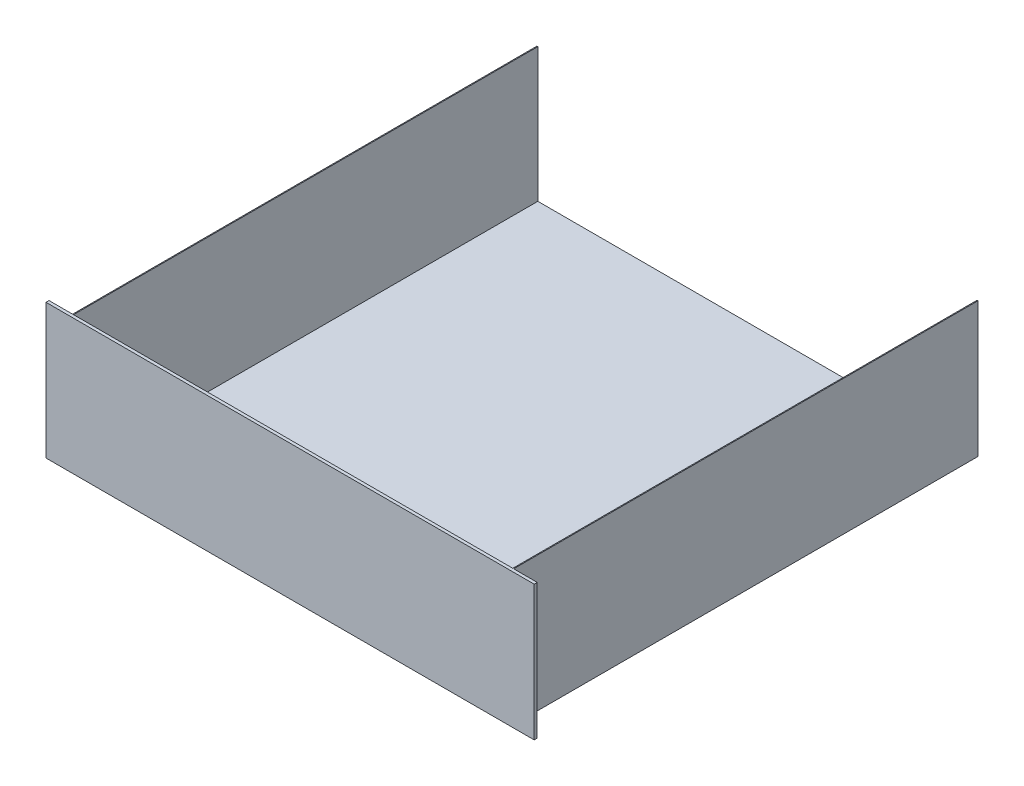
SolidWorks part; units mm, degrees
ref_plane "Front Plane" through (0, 0, 0) normal (0, 0, 1) x (1, 0, 0)
ref_plane "Top Plane" through (0, 0, 0) normal (0, 1, 0) x (1, 0, 0)
ref_plane "Right Plane" through (0, 0, 0) normal (1, 0, 0) x (0, 0, -1)
sketch "Sketch1" plane through (0, 0, 0) normal (0, 0, 1) x (1, 0, 0)
  line L1 (-241.3, 66.675) -> (241.3, 66.675)
  line L2 (-241.3, 66.675) -> (-241.3, -66.675)
  line L3 (-241.3, -66.675) -> (241.3, -66.675)
  line L4 (241.3, 66.675) -> (241.3, -66.675)
  line L5 (-241.3, 66.675) -> (241.3, -66.675) construction
  line L6 (-241.3, -66.675) -> (241.3, 66.675) construction
  point P0 (0, 0)
  dimension "D1" = 482.6
  dimension "D2" = 133.35
extrude "Front panel" add sketch "Sketch1" along normal blind 3
sketch "Sketch2" plane through (0, 0, 0) normal (0, 0, -1) x (-1, 0, 0)
  line L0 (-218, 66.675) -> (-218, -66.675)
  line L1 (-218, -66.675) -> (218, -66.675)
  line L2 (218, -66.675) -> (218, 66.675)
  line L3 (-217.1, 66.675) -> (-217.1, -65.775)
  line L4 (-217.1, -65.775) -> (217.1, -65.775)
  line L5 (217.1, -65.775) -> (217.1, 66.675)
  line L6 (241.3, -66.675) -> (-241.3, -66.675) construction
  line L7 (-218, 66.675) -> (-217.1, 66.675)
  line L8 (217.1, 66.675) -> (218, 66.675)
  point P8 (0, -66.675)
  dimension "D2" = 436
  dimension "D3" = 133.35
  dimension "D1" = 0.9
extrude "Boss-Extrude2" add sketch "Sketch2" along normal blind 459
